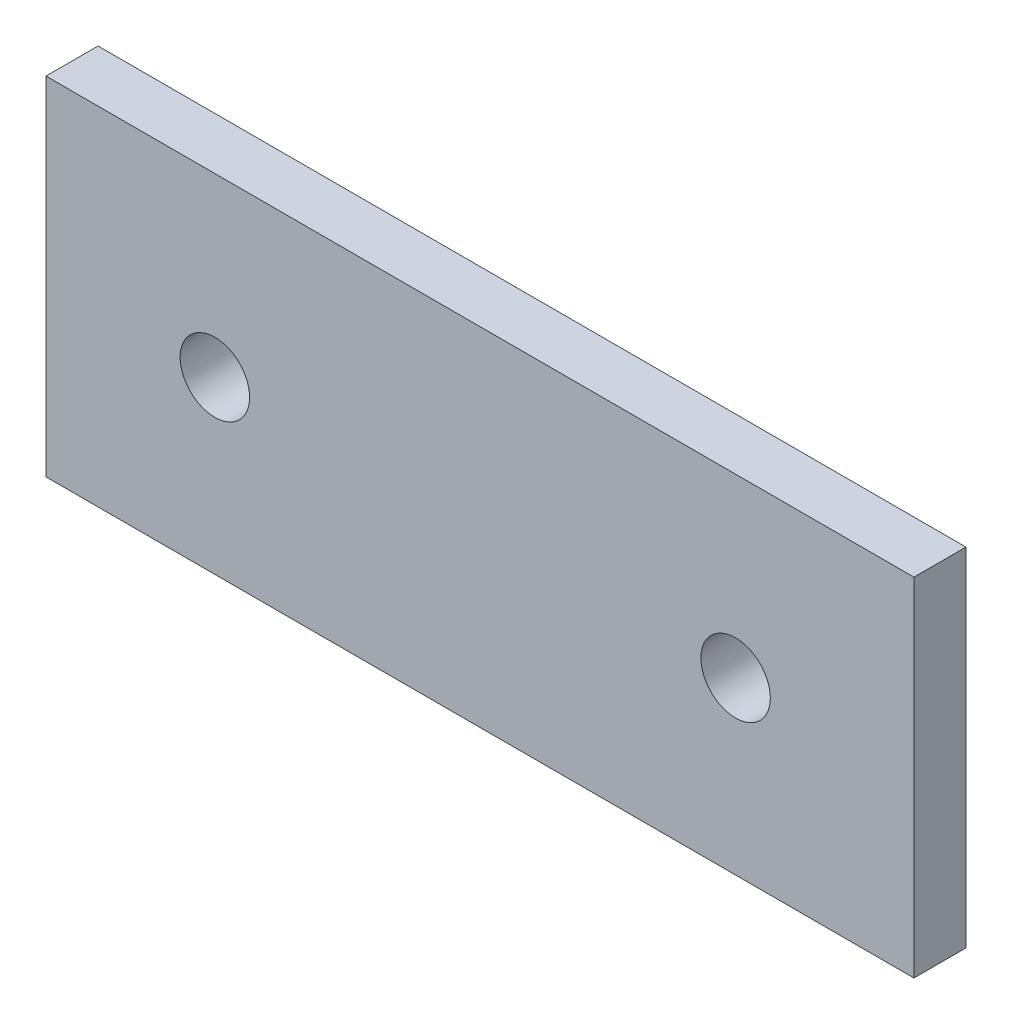
SolidWorks part; units mm, degrees
ref_plane "Front Plane" through (0, 0, 0) normal (0, 0, 1) x (1, 0, 0)
ref_plane "Top Plane" through (0, 0, 0) normal (0, 1, 0) x (1, 0, 0)
ref_plane "Right Plane" through (0, 0, 0) normal (1, 0, 0) x (0, 0, -1)
sketch "Sketch1" plane through (0, 0, 0) normal (0, 0, 1) x (1, 0, 0)
  line L0 (-67.7616, 0) -> (-37.7616, 0)
  line L2 (-77.4891, 10.1651) -> (-27.4891, 10.1651)
  line L3 (-77.4891, 10.1651) -> (-77.4891, -9.8349)
  line L4 (-77.4891, -9.8349) -> (-27.4891, -9.8349)
  line L5 (-27.4891, 10.1651) -> (-27.4891, -9.8349)
  circle A0 centre (-67.7616, 0) radius 2
  circle A1 centre (-37.7616, 0) radius 2
  dimension "D1" = 30
  dimension "D2" = 20
  dimension "D3" = 50
extrude "Boss-Extrude1" add sketch "Sketch1" along normal blind 3 contours A0 | A1 | L2 L5 L4 L3
